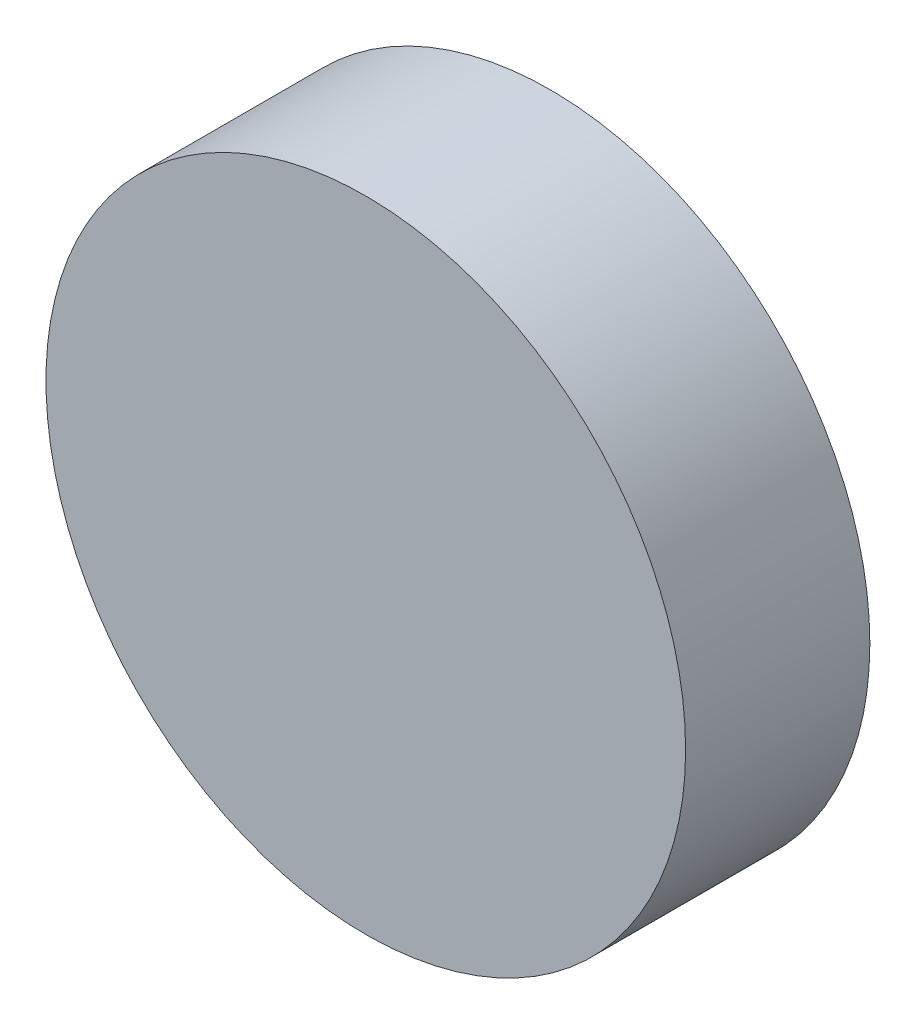
SolidWorks part; units mm, degrees
ref_plane "Front Plane" through (0, 0, 0) normal (0, 0, 1) x (1, 0, 0)
ref_plane "Top Plane" through (0, 0, 0) normal (0, 1, 0) x (1, 0, 0)
ref_plane "Right Plane" through (0, 0, 0) normal (1, 0, 0) x (0, 0, -1)
sketch "Sketch1" plane through (0, 0, 0) normal (0, 0, 1) x (1, 0, 0)
  circle A0 centre (0, 0) radius 7.9375
  dimension "D1" = 15.875
extrude "Boss-Extrude1" add sketch "Sketch1" along normal blind 4.572
